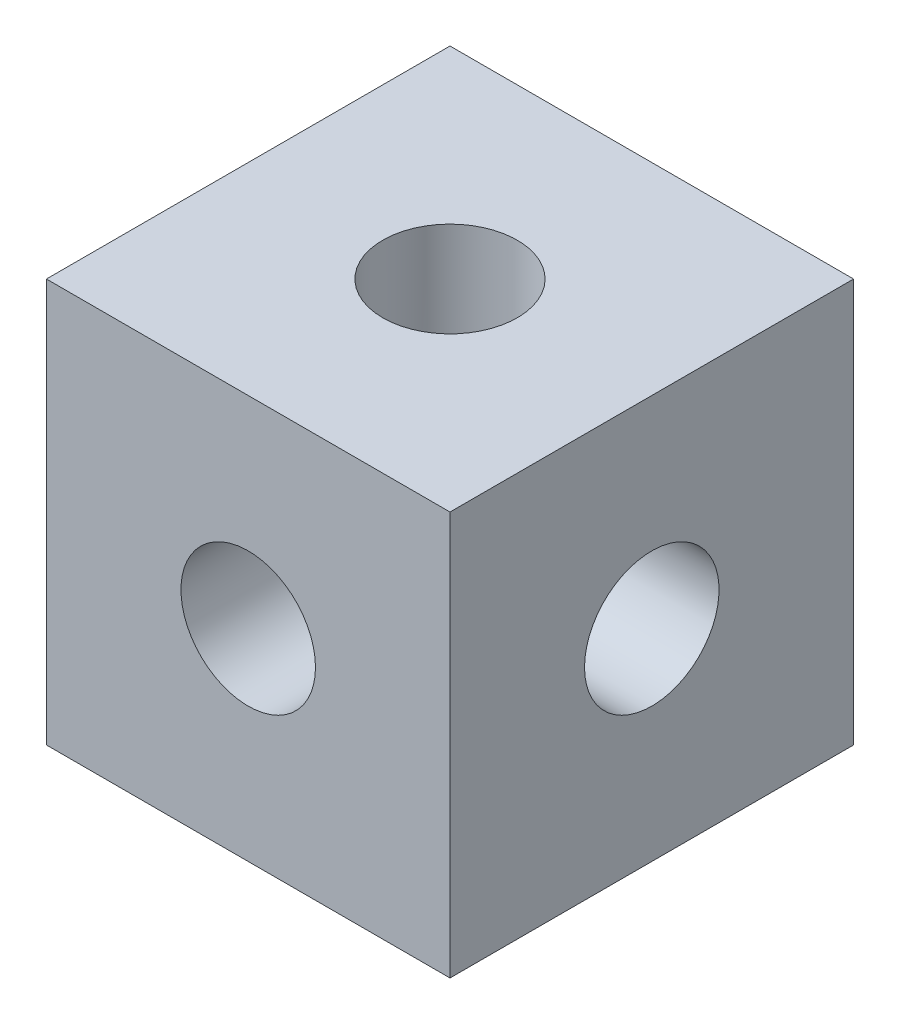
SolidWorks part; units mm, degrees
ref_plane "Front Plane" through (0, 0, 0) normal (0, 0, 1) x (1, 0, 0)
ref_plane "Top Plane" through (0, 0, 0) normal (0, 1, 0) x (1, 0, 0)
ref_plane "Right Plane" through (0, 0, 0) normal (1, 0, 0) x (0, 0, -1)
sketch "Sketch1" plane through (0, 0, 0) normal (0, 1, 0) x (1, 0, 0)
  line L1 (-7.5, -7.5) -> (7.5, -7.5)
  line L2 (-7.5, -7.5) -> (-7.5, 7.5)
  line L3 (-7.5, 7.5) -> (7.5, 7.5)
  line L4 (7.5, -7.5) -> (7.5, 7.5)
  line L5 (-7.5, -7.5) -> (7.5, 7.5) construction
  line L6 (-7.5, 7.5) -> (7.5, -7.5) construction
  point P0 (0, 0)
  dimension "D1" = 15
extrude "Boss-Extrude1" add sketch "Sketch1" along normal blind 15
sketch "Sketch3" plane through (0, 15, 0) normal (0, 1, 0) x (1, 0, 0)
  circle A0 centre (0, 0) radius 2.5
  dimension "D1" = 5
extrude "Cut-Extrude1" cut sketch "Sketch3" against normal through all contours A0
sketch "Sketch4" plane through (-7.5, 0, 0) normal (-1, 0, 0) x (0, 0, 1)
  line L0 (-7.5, 15) -> (7.5, 0) construction
  circle A0 centre (0, 7.5) radius 2.5
  point P7 (0, 7.5)
  dimension "D1" = 5
extrude "Cut-Extrude2" cut sketch "Sketch4" against normal through all contours A0
sketch "Sketch5" plane through (0, 0, 7.5) normal (0, 0, 1) x (1, 0, 0)
  line L0 (-7.5, 15) -> (7.5, 0) construction
  circle A0 centre (0, 7.5) radius 2.5
  point P7 (0, 7.5)
  dimension "D1" = 5
extrude "Cut-Extrude3" cut sketch "Sketch5" against normal through all contours A0
equation "\"D1@Sketch3\"= \"D1@Boss-Extrude1\" - 10мм"
equation "\"D1@Boss-Extrude1\"=\"D1@Sketch1\""
equation "\"D1@Sketch4\"= \"D1@Boss-Extrude1\" - 10мм"
equation "\"D1@Sketch5\"= \"D1@Boss-Extrude1\" - 10мм"
